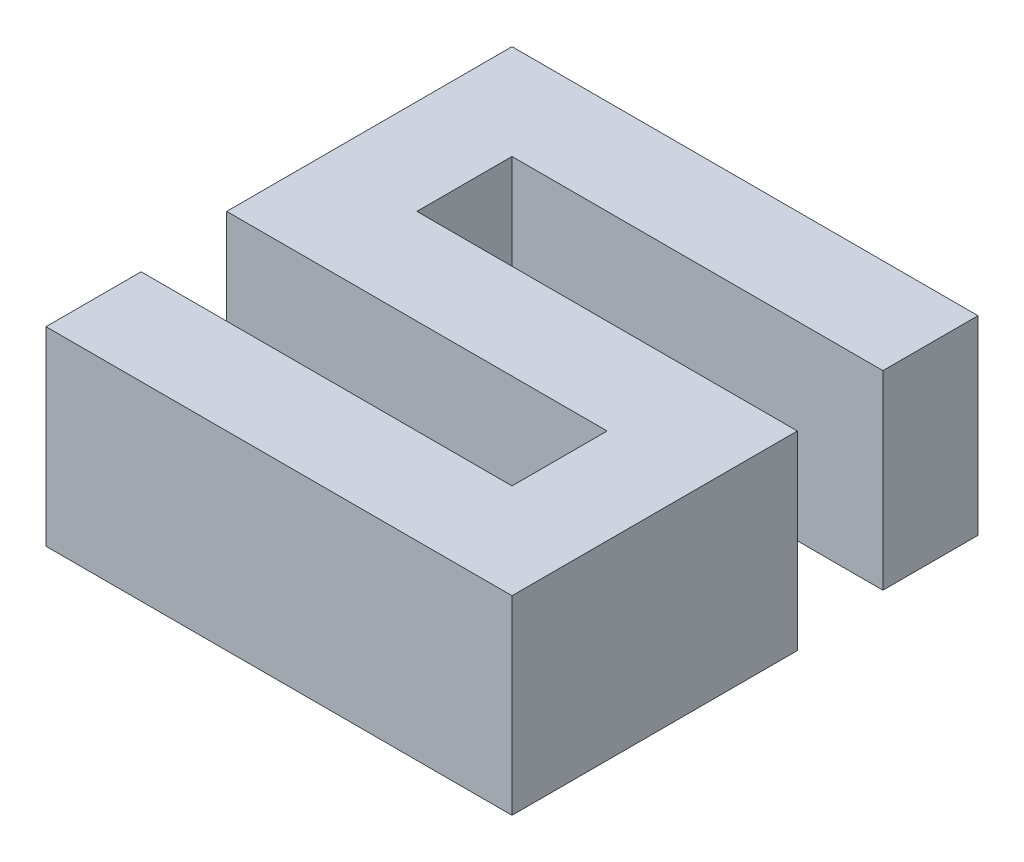
SolidWorks part; units mm, degrees
ref_plane "Front Plane" through (0, 0, 0) normal (0, 0, 1) x (1, 0, 0)
ref_plane "Top Plane" through (0, 0, 0) normal (0, 1, 0) x (1, 0, 0)
ref_plane "Right Plane" through (0, 0, 0) normal (1, 0, 0) x (0, 0, -1)
sketch "Sketch2" plane through (0, 0, 0) normal (0, 1, 0) x (1, 0, 0)
  line L0 (52.0655, 50) -> (-57.9345, 50)
  line L1 (-57.9345, 50) -> (-57.9345, 0)
  line L2 (-57.9345, 0) -> (42.0655, 0)
  line L3 (42.0655, 0) -> (42.0655, -50)
  line L4 (42.0655, -50) -> (-67.9345, -50)
  dimension "D1" = 110
  dimension "D2" = 110
  dimension "D3" = 100
  dimension "D4" = 50
  dimension "D5" = 50
extrude "Extrude-Thin1" add sketch "Sketch2" along normal blind 50 thin thin type mid plane wall 25
